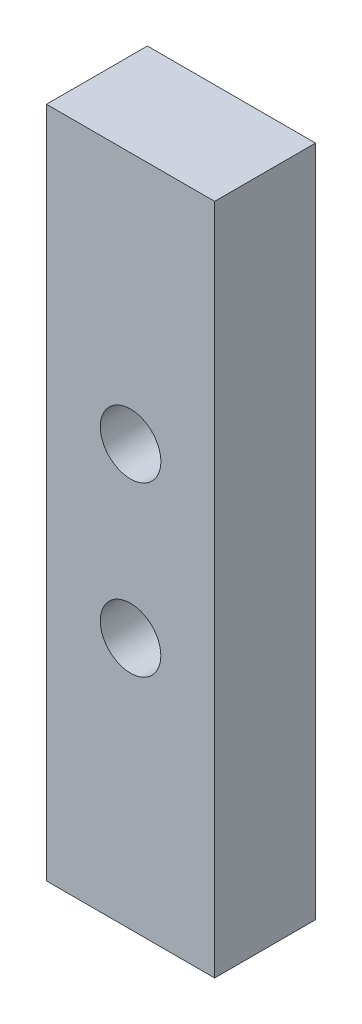
SolidWorks part; units mm, degrees
ref_plane "Front Plane" through (0, 0, 0) normal (1, 0, 0) x (0, 1, 0)
ref_plane "Top Plane" through (0, 0, 0) normal (0, 0, 1) x (0, 1, 0)
ref_plane "Right Plane" through (0, 0, 0) normal (0, 1, 0) x (-1, 0, 0)
sketch "Sketch1" plane through (0, 0, 0) normal (0, 0, 1) x (0, 1, 0)
  line L5 (-5, -2.5) -> (5, 2.5) construction
  line L6 (-5, 2.5) -> (5, -2.5) construction
  line L8 (-10, -2.5) -> (10, -2.5)
  line L9 (-10, -2.5) -> (-10, 2.5)
  line L10 (-10, 2.5) -> (10, 2.5)
  line L11 (10, -2.5) -> (10, 2.5)
  line L12 (-10, -2.5) -> (10, 2.5) construction
  line L13 (-10, 2.5) -> (10, -2.5) construction
  circle A0 centre (-2.5, 0) radius 0.9
  circle A1 centre (2.5, 0) radius 0.9
  point P0 (0, 0)
  point P12 (0, 0)
  dimension "D3" = 20
  dimension "D1" = 5
  dimension "D2" = 10
extrude "Boss-Extrude1" add sketch "Sketch1" along normal blind 3
